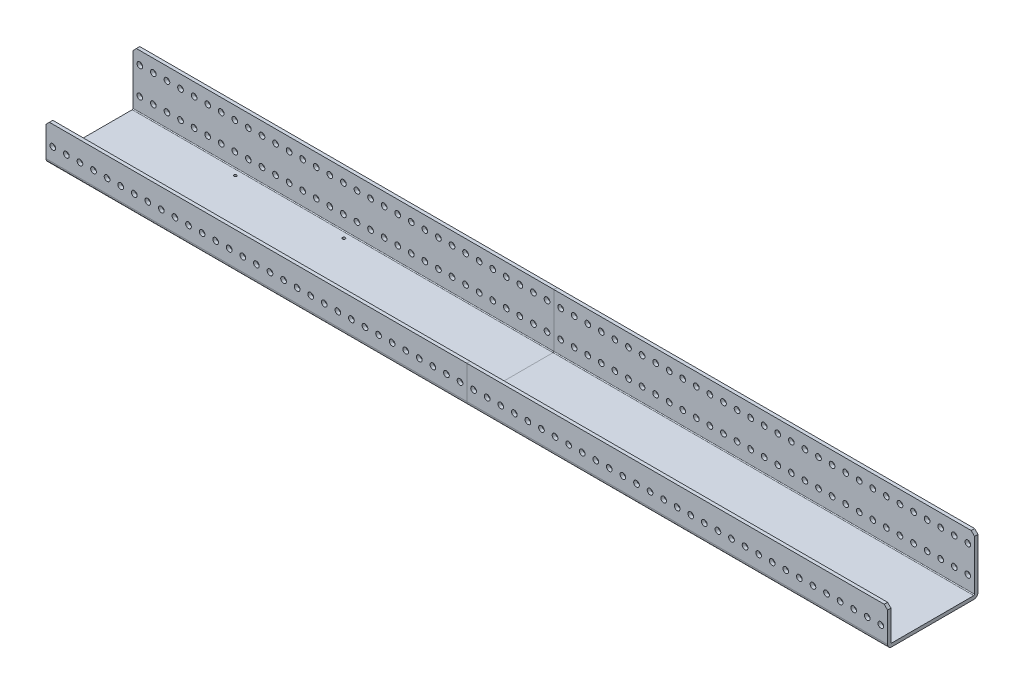
SolidWorks part; units mm, degrees
ref_plane "Front Plane" through (0, 0, 0) normal (0, 0, 1) x (1, 0, 0)
ref_plane "Top Plane" through (0, 0, 0) normal (0, 1, 0) x (1, 0, 0)
ref_plane "Right Plane" through (0, 0, 0) normal (1, 0, 0) x (0, 0, -1)
ref_plane "Plane1" through (0, 53.975, 0) normal (0, 1, 0) x (1, 0, 0)
sketch "Sketch1" plane through (0, 53.975, 0) normal (0, 1, 0) x (1, 0, 0)
  line L0 (787.4, 81.407) -> (0, 81.407)
  line L1 (0, 81.407) -> (0, -3.175)
  line L2 (0, -3.175) -> (787.4, -3.175)
  line L3 (787.4, -3.175) -> (787.4, 81.407)
extrude "Boss-Extrude1" add sketch "Sketch1" against normal blind 53.975
sketch "Sketch2" plane through (787.4, 0, 0) normal (1, 0, 0) x (0, 0, -1)
  line L0 (-3.175, 3.175) -> (78.232, 3.175)
  line L1 (78.232, 3.175) -> (78.232, 53.975)
  line L2 (78.232, 53.975) -> (-3.175, 53.975)
  line L3 (-3.175, 53.975) -> (-3.175, 3.175)
extrude "Cut-Extrude1" cut sketch "Sketch2" against normal through all
sketch "Sketch3" plane through (0, 3.175, 0) normal (0, 1, 0) x (-1, 0, 0)
  line L0 (0, 0) -> (-787.4, 0)
  line L1 (-787.4, 0) -> (-787.4, 3.175)
  line L2 (-787.4, 3.175) -> (0, 3.175)
  line L3 (0, 3.175) -> (0, 0)
extrude "Boss-Extrude2" add sketch "Sketch3" along normal blind 31.75
hole_wizard "#2 Clearance Hole1" positions "Sketch5" profile "Sketch4" hole size "#2" standard "ANSI Inch"
sketch "Sketch5" plane through (0, 3.175, 0) normal (0, 1, 0) x (1, 0, 0)
  point P0 (101.6, 5.842)
  point P1 (203.2, 5.842)
  point P2 (203.2, 72.39)
  point P3 (101.6, 72.39)
sketch "Sketch4" plane through (101.6, 3.175, -5.842) normal (1, 0, 0) x (0, 0, 1)
  line L0 (0, 0) -> (0, 3.175)
  line L1 (0, 3.175) -> (1.27, 3.175)
  line L2 (1.27, 3.175) -> (1.27, 0)
  line L5 (1.27, 0) -> (0, 0)
  line L11 (0, -6.35) -> (0, 107.95) construction
  dimension "Thru Hole Dia." = 2.54
  dimension "Thru Hole Depth" = 3.175
hole_wizard "#10 Clearance Hole1" positions "Sketch7" profile "Sketch6" hole size "#10" standard "ANSI Inch"
sketch "Sketch7" plane through (0, 0, 3.175) normal (0, 0, 1) x (1, 0, 0)
  point P0 (768.35, 16.637)
  point P1 (781.05, 16.637)
  point P2 (755.65, 16.637)
  point P3 (742.95, 16.637)
  point P4 (730.25, 16.637)
  point P5 (717.55, 16.637)
  point P6 (704.85, 16.637)
  point P7 (692.15, 16.637)
  point P8 (679.45, 16.637)
  point P9 (666.75, 16.637)
  point P10 (654.05, 16.637)
  point P11 (641.35, 16.637)
  point P12 (628.65, 16.637)
  point P13 (615.95, 16.637)
  point P14 (603.25, 16.637)
  point P15 (590.55, 16.637)
  point P16 (577.85, 16.637)
  point P17 (565.15, 16.637)
  point P18 (552.45, 16.637)
  point P19 (539.75, 16.637)
  point P20 (527.05, 16.637)
  point P21 (514.35, 16.637)
  point P22 (501.65, 16.637)
  point P23 (488.95, 16.637)
  point P24 (476.25, 16.637)
  point P25 (463.55, 16.637)
  point P26 (450.85, 16.637)
  point P27 (438.15, 16.637)
  point P28 (425.45, 16.637)
  point P29 (412.75, 16.637)
  point P30 (400.05, 16.637)
  point P31 (387.35, 16.637)
  point P32 (374.65, 16.637)
  point P33 (361.95, 16.637)
  point P34 (349.25, 16.637)
  point P35 (336.55, 16.637)
  point P36 (323.85, 16.637)
  point P37 (311.15, 16.637)
  point P38 (298.45, 16.637)
  point P39 (285.75, 16.637)
  point P40 (273.05, 16.637)
  point P41 (260.35, 16.637)
  point P42 (247.65, 16.637)
  point P43 (234.95, 16.637)
  point P44 (222.25, 16.637)
  point P45 (209.55, 16.637)
  point P46 (196.85, 16.637)
  point P47 (184.15, 16.637)
  point P48 (171.45, 16.637)
  point P49 (158.75, 16.637)
  point P50 (146.05, 16.637)
  point P51 (133.35, 16.637)
  point P52 (120.65, 16.637)
  point P53 (107.95, 16.637)
  point P54 (95.25, 16.637)
  point P55 (82.55, 16.637)
  point P56 (69.85, 16.637)
  point P57 (57.15, 16.637)
  point P58 (44.45, 16.637)
  point P59 (31.75, 16.637)
  point P60 (19.05, 16.637)
  point P61 (6.35, 16.637)
sketch "Sketch6" plane through (768.35, 16.637, 3.175) normal (1, 0, 0) x (0, -1, 0)
  line L0 (0, 0) -> (0, 3.175)
  line L1 (0, 3.175) -> (2.667, 3.175)
  line L2 (2.667, 3.175) -> (2.667, 0)
  line L5 (2.667, 0) -> (0, 0)
  line L11 (0, -6.35) -> (0, 107.95) construction
  dimension "Thru Hole Dia." = 5.334
  dimension "Thru Hole Depth" = 3.175
hole_wizard "#10 Clearance Hole2" positions "Sketch9" profile "Sketch8" hole size "#10" standard "ANSI Inch"
sketch "Sketch9" plane through (0, 0, -81.407) normal (0, 0, -1) x (-1, 0, 0)
  point P0 (-768.35, 42.037)
  point P1 (-781.05, 42.037)
  point P2 (-768.35, 16.637)
  point P3 (-781.05, 16.637)
  point P4 (-755.65, 16.637)
  point P5 (-742.95, 16.637)
  point P6 (-730.25, 16.637)
  point P7 (-717.55, 16.637)
  point P8 (-704.85, 16.637)
  point P9 (-692.15, 16.637)
  point P10 (-679.45, 16.637)
  point P11 (-666.75, 16.637)
  point P12 (-654.05, 16.637)
  point P13 (-641.35, 16.637)
  point P14 (-628.65, 16.637)
  point P15 (-615.95, 16.637)
  point P16 (-603.25, 16.637)
  point P17 (-590.55, 16.637)
  point P18 (-577.85, 16.637)
  point P19 (-565.15, 16.637)
  point P20 (-552.45, 16.637)
  point P21 (-539.75, 16.637)
  point P22 (-527.05, 16.637)
  point P23 (-514.35, 16.637)
  point P24 (-501.65, 16.637)
  point P25 (-488.95, 16.637)
  point P26 (-476.25, 16.637)
  point P27 (-463.55, 16.637)
  point P28 (-450.85, 16.637)
  point P29 (-438.15, 16.637)
  point P30 (-425.45, 16.637)
  point P31 (-412.75, 16.637)
  point P32 (-400.05, 16.637)
  point P33 (-387.35, 16.637)
  point P34 (-374.65, 16.637)
  point P35 (-361.95, 16.637)
  point P36 (-349.25, 16.637)
  point P37 (-336.55, 16.637)
  point P38 (-323.85, 16.637)
  point P39 (-311.15, 16.637)
  point P40 (-298.45, 16.637)
  point P41 (-285.75, 16.637)
  point P42 (-273.05, 16.637)
  point P43 (-260.35, 16.637)
  point P44 (-247.65, 16.637)
  point P45 (-234.95, 16.637)
  point P46 (-222.25, 16.637)
  point P47 (-209.55, 16.637)
  point P48 (-196.85, 16.637)
  point P49 (-184.15, 16.637)
  point P50 (-171.45, 16.637)
  point P51 (-158.75, 16.637)
  point P52 (-146.05, 16.637)
  point P53 (-133.35, 16.637)
  point P54 (-120.65, 16.637)
  point P55 (-107.95, 16.637)
  point P56 (-95.25, 16.637)
  point P57 (-82.55, 16.637)
  point P58 (-69.85, 16.637)
  point P59 (-57.15, 16.637)
  point P60 (-44.45, 16.637)
  point P61 (-31.75, 16.637)
  point P62 (-19.05, 16.637)
  point P63 (-6.35, 16.637)
  point P64 (-755.65, 42.037)
  point P65 (-742.95, 42.037)
  point P66 (-730.25, 42.037)
  point P67 (-717.55, 42.037)
  point P68 (-704.85, 42.037)
  point P69 (-692.15, 42.037)
  point P70 (-679.45, 42.037)
  point P71 (-666.75, 42.037)
  point P72 (-654.05, 42.037)
  point P73 (-641.35, 42.037)
  point P74 (-628.65, 42.037)
  point P75 (-615.95, 42.037)
  point P76 (-603.25, 42.037)
  point P77 (-590.55, 42.037)
  point P78 (-577.85, 42.037)
  point P79 (-565.15, 42.037)
  point P80 (-552.45, 42.037)
  point P81 (-539.75, 42.037)
  point P82 (-527.05, 42.037)
  point P83 (-514.35, 42.037)
  point P84 (-501.65, 42.037)
  point P85 (-488.95, 42.037)
  point P86 (-476.25, 42.037)
  point P87 (-463.55, 42.037)
  point P88 (-450.85, 42.037)
  point P89 (-438.15, 42.037)
  point P90 (-425.45, 42.037)
  point P91 (-412.75, 42.037)
  point P92 (-400.05, 42.037)
  point P93 (-387.35, 42.037)
  point P94 (-374.65, 42.037)
  point P95 (-361.95, 42.037)
  point P96 (-349.25, 42.037)
  point P97 (-336.55, 42.037)
  point P98 (-323.85, 42.037)
  point P99 (-311.15, 42.037)
  point P100 (-298.45, 42.037)
  point P101 (-285.75, 42.037)
  point P102 (-273.05, 42.037)
  point P103 (-260.35, 42.037)
  point P104 (-247.65, 42.037)
  point P105 (-234.95, 42.037)
  point P106 (-222.25, 42.037)
  point P107 (-209.55, 42.037)
  point P108 (-196.85, 42.037)
  point P109 (-184.15, 42.037)
  point P110 (-171.45, 42.037)
  point P111 (-158.75, 42.037)
  point P112 (-146.05, 42.037)
  point P113 (-133.35, 42.037)
  point P114 (-120.65, 42.037)
  point P115 (-107.95, 42.037)
  point P116 (-95.25, 42.037)
  point P117 (-82.55, 42.037)
  point P118 (-69.85, 42.037)
  point P119 (-57.15, 42.037)
  point P120 (-44.45, 42.037)
  point P121 (-31.75, 42.037)
  point P122 (-19.05, 42.037)
  point P123 (-6.35, 42.037)
sketch "Sketch8" plane through (768.35, 42.037, -81.407) normal (1, 0, 0) x (0, 1, 0)
  line L0 (0, 0) -> (0, 84.582)
  line L1 (0, 84.582) -> (2.667, 84.582)
  line L2 (2.667, 84.582) -> (2.667, 0)
  line L5 (2.667, 0) -> (0, 0)
  line L11 (0, -6.35) -> (0, 107.95) construction
  dimension "Thru Hole Dia." = 5.334
  dimension "Thru Hole Depth" = 84.582
chamfer "Chamfer1" distance 3.175 angle 45 4 edges at (787.4, 53.975, -79.8195) (0, 34.925, 1.5875) (0, 53.975, -79.8195) (787.4, 34.925, 1.5875)
fillet "Fillet1" radius 0.762 2 edges at (393.7, 3.175, 0) (393.7, 3.175, -78.232)
fillet "Fillet2" radius 3.937 2 edges at (393.7, 0, -81.407) (393.7, 0, 3.175)
sketch "Sketch11" plane through (0, 53.975, 0) normal (0, 1, 0) x (1, 0, 0)
  line L0 (393.7, 81.407) -> (393.7, -54.3651)
  line L1 (784.225, 81.407) -> (3.175, 81.407) construction
split "Split2" trim tools "Sketch11" bodies to split 108 resulting bodies 110 111
